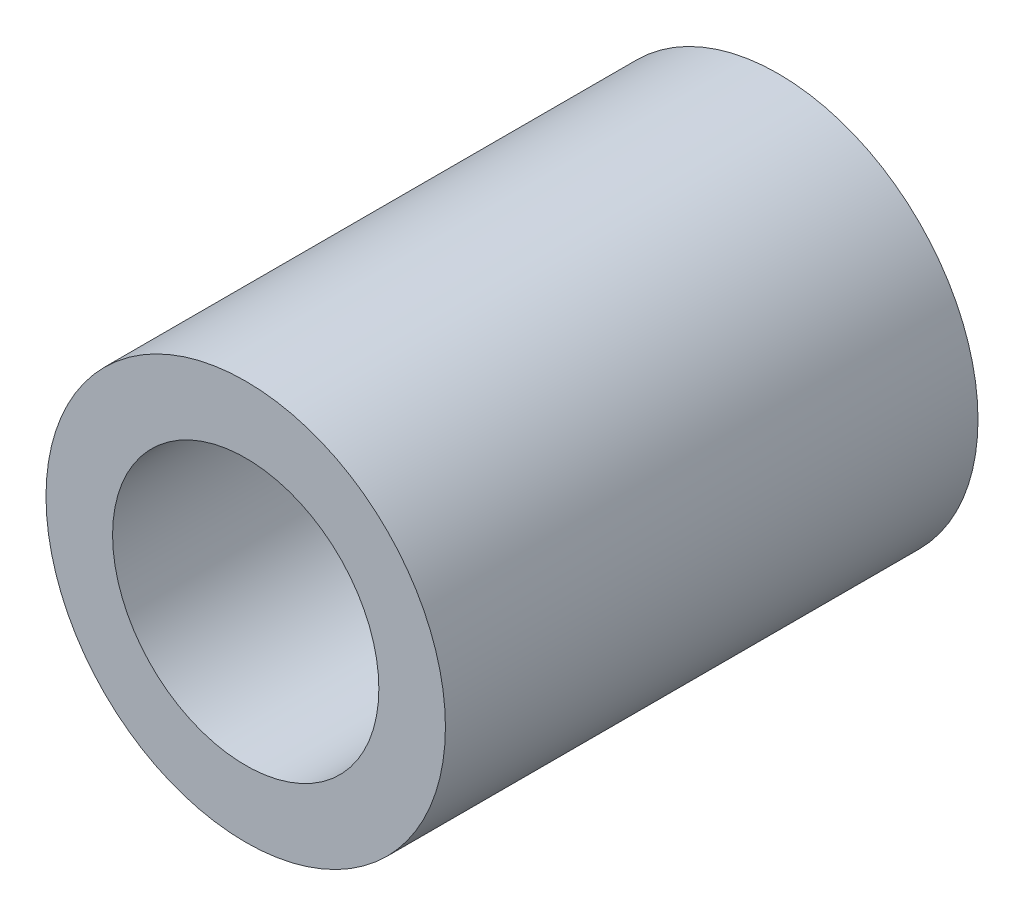
SolidWorks part; units mm, degrees
ref_plane "Спереди" through (0, 0, 0) normal (0, 0, 1) x (1, 0, 0)
ref_plane "Сверху" through (0, 0, 0) normal (0, 1, 0) x (1, 0, 0)
ref_plane "Справа" through (0, 0, 0) normal (1, 0, 0) x (0, 0, -1)
ref_plane "Плоскость4" through (0, 0, 1) normal (0, 0, 1) x (1, 0, 0)
sketch "Эскиз1" plane through (0, 0, 1) normal (0, 0, 1) x (1, 0, 0)
  circle A0 centre (135, 20) radius 2
  circle A1 centre (135, 20) radius 3
  dimension "D1" = 6
  dimension "D2" = 4
extrude "Бобышка-Вытянуть1" add sketch "Эскиз1" against normal up to surface (8 mm away)
